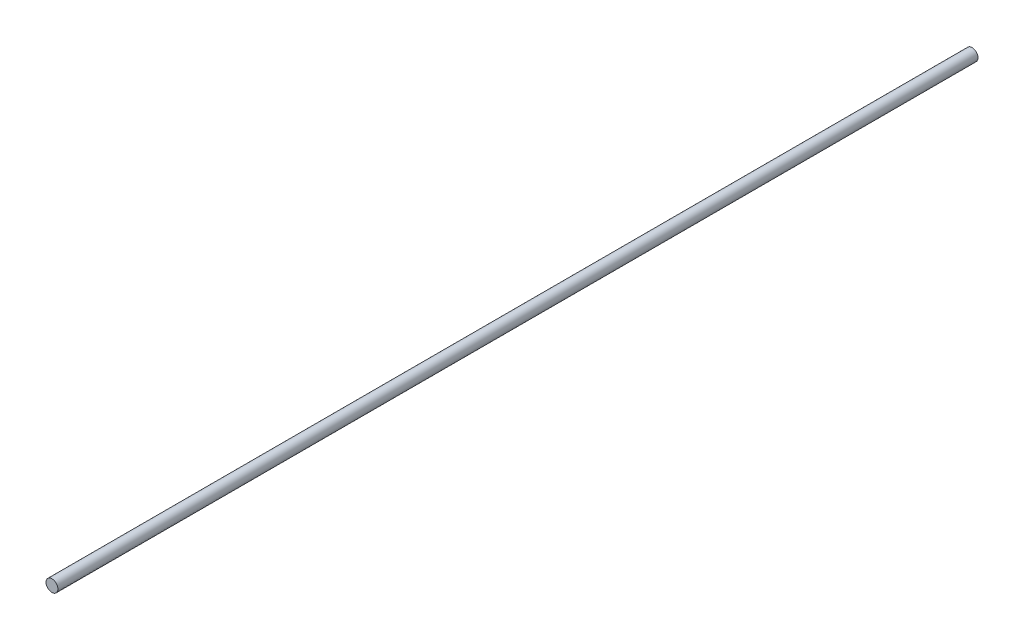
SolidWorks part; units mm, degrees
material "Zoltek Panex 33"
ref_plane "Front Plane" through (0, 0, 0) normal (0, 0, 1) x (1, 0, 0)
ref_plane "Top Plane" through (0, 0, 0) normal (0, 1, 0) x (1, 0, 0)
ref_plane "Right Plane" through (0, 0, 0) normal (1, 0, 0) x (0, 0, -1)
sketch "Sketch1" plane through (0, 0, 0) normal (0, 0, 1) x (1, 0, 0)
  circle A0 centre (0, 0) radius 1.5875
  dimension "D1" = 3.175
extrude "Boss-Extrude1" add sketch "Sketch1" along normal blind 245.95
